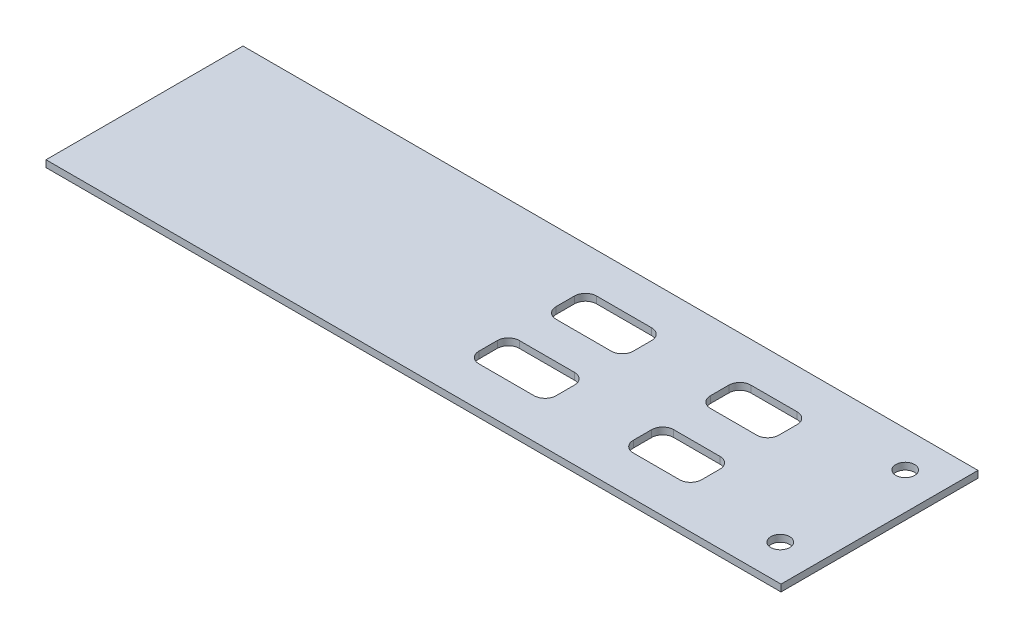
SolidWorks part; units mm, degrees
ref_plane "Front Plane" through (0, 0, 0) normal (0, 0, 1) x (1, 0, 0)
ref_plane "Top Plane" through (0, 0, 0) normal (0, 1, 0) x (1, 0, 0)
ref_plane "Right Plane" through (0, 0, 0) normal (1, 0, 0) x (0, 0, -1)
sketch "Sketch1" plane through (0, 0, 0) normal (0, 1, 0) x (1, 0, 0)
  line L1 (0, 0) -> (152.4, 0)
  line L2 (0, 0) -> (0, 68.072)
  line L3 (0, 68.072) -> (152.4, 68.072)
  line L4 (152.4, 0) -> (152.4, 68.072)
  dimension "D1" = 68.072
  dimension "D2" = 152.4
extrude "Boss-Extrude1" add sketch "Sketch1" along normal blind 2.3622
sketch "Sketch2" plane through (0, 2.3622, 0) normal (0, 1, 0) x (1, 0, 0)
  line L0 (0, 68.072) -> (0, 0) construction
  line L1 (30.48, 54.356) -> (57.15, 54.356)
  line L2 (30.48, 54.356) -> (30.48, 40.386)
  line L3 (30.48, 40.386) -> (57.15, 40.386)
  line L4 (57.15, 54.356) -> (57.15, 40.386)
  line L5 (83.82, 54.356) -> (107.442, 54.356)
  line L6 (83.82, 54.356) -> (83.82, 40.386)
  line L7 (83.82, 40.386) -> (107.442, 40.386)
  line L8 (107.442, 54.356) -> (107.442, 40.386)
  line L9 (152.4, 0) -> (152.4, 68.072) construction
  line L10 (30.48, 27.686) -> (57.15, 27.686)
  line L11 (30.48, 27.686) -> (30.48, 13.716)
  line L12 (30.48, 13.716) -> (57.15, 13.716)
  line L13 (57.15, 27.686) -> (57.15, 13.716)
  line L14 (83.82, 27.686) -> (107.442, 27.686)
  line L15 (83.82, 27.686) -> (83.82, 13.716)
  line L16 (83.82, 13.716) -> (107.442, 13.716)
  line L17 (107.442, 27.686) -> (107.442, 13.716)
  point P10 (83.82, 47.371)
  point P17 (0, 34.036)
  dimension "D1" = 26.67
  dimension "D2" = 23.622
  dimension "D3" = 44.958
  dimension "D4" = 13.97
  dimension "D5" = 12.7
  dimension "D6" = 6.35
  dimension "D7" = 30.48
extrude "Cut-Extrude1" cut sketch "Sketch2" against normal through all
fillet "Fillet1" radius 3.81 16 edges at (83.82, 1.1811, -13.716) (83.82, 1.1811, -40.386) (30.48, 1.1811, -40.386) (30.48, 1.1811, -13.716) (107.442, 1.1811, -13.716) (57.15, 1.1811, -40.386) (57.15, 1.1811, -13.716) (107.442, 1.1811, -40.386) (107.442, 1.1811, -27.686) (107.442, 1.1811, -54.356) (57.15, 1.1811, -27.686) (57.15, 1.1811, -54.356) (30.48, 1.1811, -27.686) (83.82, 1.1811, -27.686) (83.82, 1.1811, -54.356) (30.48, 1.1811, -54.356)
sketch "Sketch4" plane through (0, 0, 0) normal (-1, 0, 0) x (0, 0, 1)
  line L1 (-68.072, 2.3622) -> (0, 2.3622)
  line L2 (-68.072, 2.3622) -> (-68.072, 0)
  line L3 (-68.072, 0) -> (0, 0)
  line L4 (0, 2.3622) -> (0, 0)
extrude "Boss-Extrude2" add sketch "Sketch4" along normal blind 101.6
sketch "Sketch5" plane through (0, 0, 0) normal (0, -1, 0) x (1, 0, 0)
  line L0 (152.4, 0) -> (152.4, -68.072) construction
  line L3 (139.7, -12.446) -> (139.7, -55.626) construction
  circle A0 centre (139.7, -12.446) radius 3.2639
  circle A1 centre (139.7, -55.626) radius 3.2639
  point P6 (139.7, -34.036)
  point P7 (152.4, -34.036)
  point P8 (0, 0)
  dimension "D1" = 6.5278
  dimension "D2" = 12.7
  dimension "D3" = 43.18
extrude "Cut-Extrude2" cut sketch "Sketch5" against normal through all
